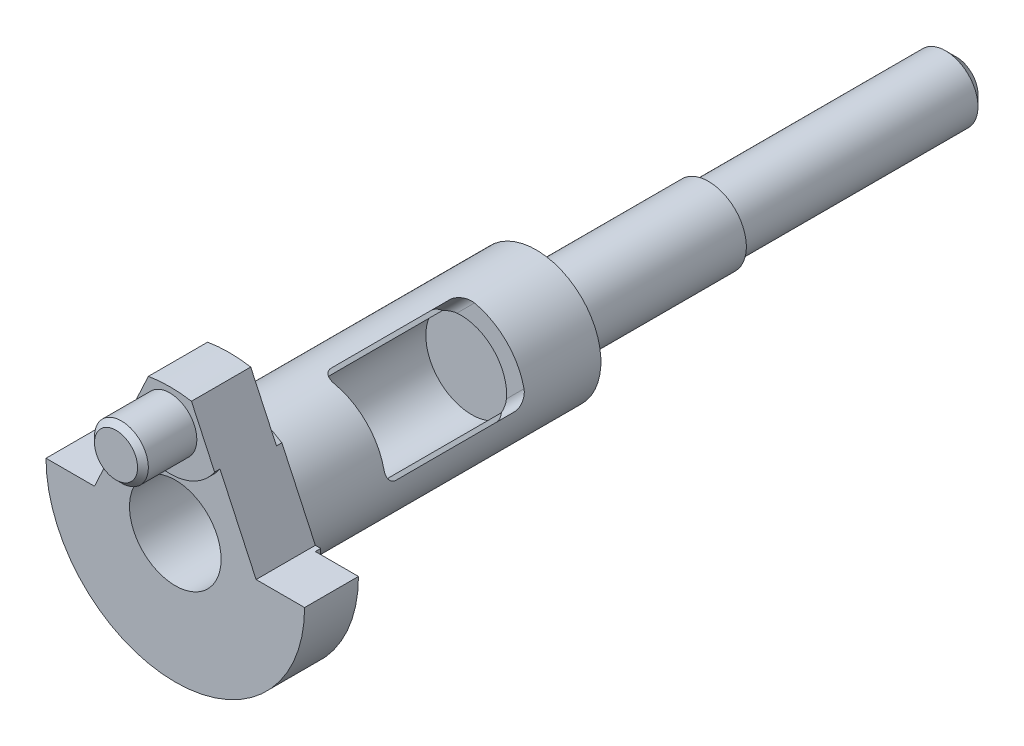
SolidWorks part; units mm, degrees
ref_plane "Plan1" through (0, 0, 0) normal (0, 0, 1) x (1, 0, 0)
ref_plane "Plan2" through (0, 0, 0) normal (0, 1, 0) x (1, 0, 0)
ref_plane "Plan3" through (0, 0, 0) normal (1, 0, 0) x (0, 0, -1)
sketch "Esquisse9" plane through (0, 0, 0) normal (1, 0, 0) x (0, 0, -1)
  line L0 (76, 0) -> (-25, 0) construction
ref_plane "Plan4" through (0, 0, 0) normal (0.7071, -0.7071, 0) x (0.7071, 0.7071, 0)
sketch "Esquisse1" plane through (0, 0, 0) normal (0, 0, 1) x (1, 0, 0)
  line L2 (2, 11.8322) -> (7.5, 0)
  line L5 (12, 0) -> (7.5, 0)
  line L8 (-2, 11.8322) -> (-7.5, 0)
  line L9 (-7.5, 0) -> (-12, 0)
  arc A0 (2, 11.8322) -> (-2, 11.8322) centre (0, 0) ccw
  arc A1 (-12, 0) -> (12, 0) centre (0, 0) ccw
  dimension "D1" = 24
extrude "Base-Extrusion" add sketch "Esquisse1" along normal blind 5
sketch "Esquisse2" plane through (0, 0, 5) normal (0, 0, 1) x (1, 0, 0)
  line L0 (0, 16) -> (0, -14) construction
  line L1 (14, 0) -> (-18, 0) construction
  line L2 (9, 10) -> (-7, 10) construction
  line L3 (2, 11.8322) -> (7.5, 0) construction
  line L4 (-2, 11.8322) -> (-7.5, 0) construction
  line L5 (2, 11.8322) -> (4.1488, 7.2094)
  line L6 (-2, 11.8322) -> (-4.1488, 7.2094)
  arc A0 (-4.1488, 7.2094) -> (4.1488, 7.2094) centre (0, 10) ccw
  arc A1 (2, 11.8322) -> (-2, 11.8322) centre (0, 0) ccw construction
  arc A2 (2, 11.8322) -> (-2, 11.8322) centre (0, 0) ccw
  dimension "D2" = 10
  dimension "D1" = 10
extrude "Boss.-Extru.1" add sketch "Esquisse2" along normal blind 0.5
sketch "Esquisse3" plane through (0, 0, 5.5) normal (0, 0, 1) x (1, 0, 0)
  line L0 (14, 0) -> (-16, 0) construction
  line L1 (0, 14) -> (0, -14) construction
  line L2 (15, 9) -> (-11, 9) construction
  circle A0 centre (0, 9) radius 2.5
  dimension "D2" = 5
  dimension "D1" = 9
extrude "Boss.-Extru.2" add sketch "Esquisse3" along normal blind 5
sketch "Esquisse4" plane through (0, 0, 0) normal (0, 0, -1) x (-1, 0, 0)
  line L0 (-12, 0) -> (-7.5, 0) construction
  line L1 (-2, 11.8322) -> (-7.5, 0) construction
  line L2 (2, 11.8322) -> (7.5, 0) construction
  line L3 (7.5, 0) -> (12, 0) construction
  line L4 (-8, 0) -> (-7.5, 0)
  line L5 (-4.3918, 6.6867) -> (-7.5, 0)
  line L6 (4.3918, 6.6867) -> (7.5, 0)
  line L7 (7.5, 0) -> (8, 0)
  arc A0 (4.3918, 6.6867) -> (-4.3918, 6.6867) centre (0, 0) ccw
  arc A1 (-8, 0) -> (8, 0) centre (0, 0) ccw
  dimension "D1" = 16
extrude "Boss.-Extru.3" add sketch "Esquisse4" along normal blind 0.5
sketch "Esquisse5" plane through (0, 0, -0.5) normal (0, 0, -1) x (-1, 0, 0)
  circle A0 centre (0, 0) radius 6
  dimension "D1" = 12
extrude "Boss.-Extru.4" add sketch "Esquisse5" along normal blind 28
sketch "Esquisse6" plane through (0, 0, -28.5) normal (0, 0, -1) x (-1, 0, 0)
  circle A0 centre (0, 0) radius 3.5
  circle A1 centre (0, 0) radius 6 construction
  dimension "D1" = 7
extrude "Boss.-Extru.5" add sketch "Esquisse6" along normal blind 16
sketch "Esquisse7" plane through (0, 0, -44.5) normal (0, 0, -1) x (-1, 0, 0)
  circle A0 centre (0, 0) radius 3
  dimension "D1" = 6
extrude "Boss.-Extru.6" add sketch "Esquisse7" along normal blind 23
chamfer "Chanfrein1" distance 1 angle 45
sketch "Esquisse8" plane through (0, 0, 5.5) normal (0, 0, 1) x (1, 0, 0)
  circle A0 centre (0, 0) radius 4.25
  arc A1 (-12, 0) -> (12, 0) centre (0, 0) ccw construction
  dimension "D1" = 8.5
extrude "Enlèv. mat.-Extru.1" cut sketch "Esquisse8" against normal blind 28
ref_plane "Plan5" through (4.2426, 4.2426, -14.5) normal (0.7071, 0.7071, 0) x (-0.7071, 0.7071, 0)
sketch "Esquisse12" plane through (4.2426, 4.2426, -14.5) normal (0.7071, 0.7071, 0) x (-0.7071, 0.7071, 0)
  line L0 (-3.25, 6) -> (3.25, 6)
  line L1 (4.25, 5) -> (4.25, -6)
  line L2 (3.25, -7) -> (-3.25, -7)
  line L3 (-4.25, -6) -> (-4.25, 5)
  line L4 (-6, -14) -> (6, -14) construction
  line L5 (0, -61.5) -> (0, 39.5) construction
  arc A0 (4.25, 5) -> (3.25, 6) centre (3.25, 5) ccw
  arc A1 (-4.25, 5) -> (-3.25, 6) centre (-3.25, 5) cw
  arc A2 (-3.25, -7) -> (-4.25, -6) centre (-3.25, -6) cw
  arc A3 (4.25, -6) -> (3.25, -7) centre (3.25, -6) cw
  point P10 (4.25, 6)
  point P17 (4.25, -7)
  dimension "D5" = 1
  dimension "D1" = 7
  dimension "D2" = 4.25
  dimension "D3" = 4.25
  dimension "D4" = 13
extrude "Enlèv. mat.-Extru.4" cut sketch "Esquisse12" against normal blind 4.25
chamfer "Chanfrein2" distance 0.5 angle 45
